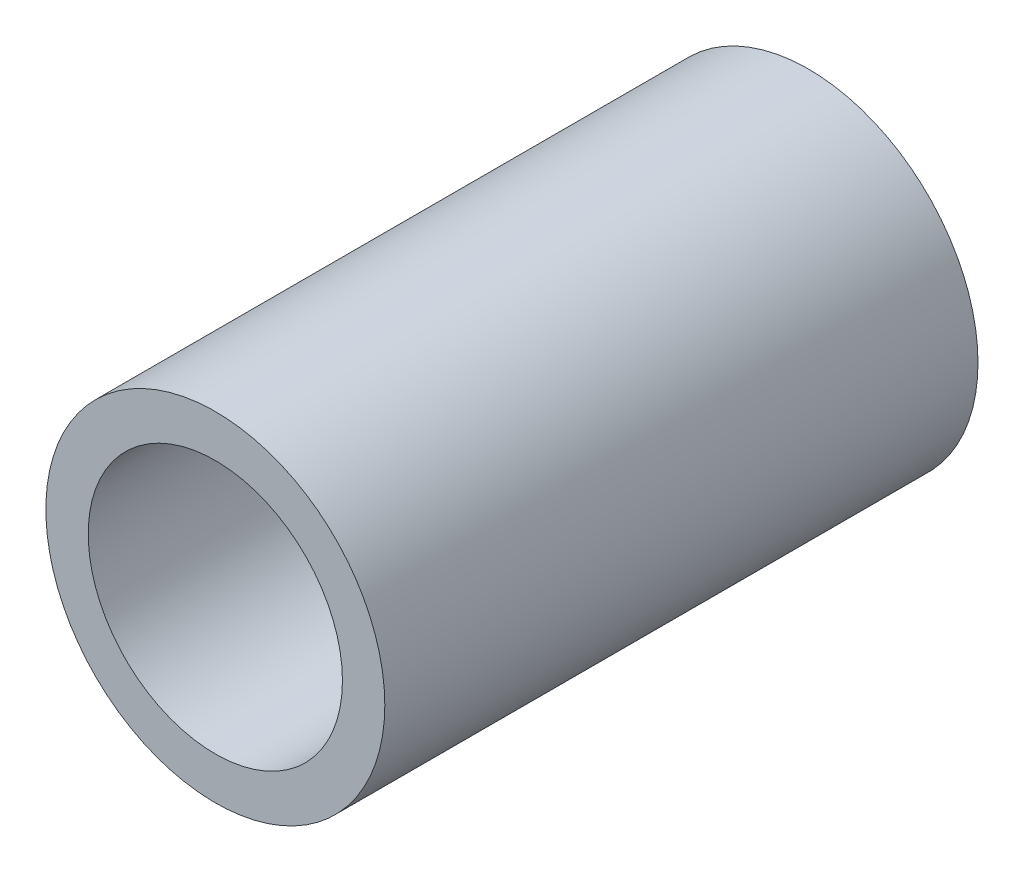
SolidWorks part; units mm, degrees
ref_plane "Front Plane" through (0, 0, 0) normal (0, 0, 1) x (1, 0, 0)
ref_plane "Top Plane" through (0, 0, 0) normal (0, 1, 0) x (1, 0, 0)
ref_plane "Right Plane" through (0, 0, 0) normal (1, 0, 0) x (0, 0, -1)
sketch "Sketch1" plane through (0, 0, 0) normal (0, 0, 1) x (1, 0, 0)
  circle A0 centre (0, 0) radius 6.35
  circle A1 centre (0, 0) radius 4.7625
  dimension "D1" = 12.7
  dimension "ID" = 9.525
extrude "Extrude1" add sketch "Sketch1" along normal mid plane 22.225
sketch "Sketch2" plane through (0, 0, 0) normal (1, 0, 0) x (0, 0, -1)
  line L0 (-11.1125, -4.7625) -> (11.1125, -4.7625) construction
  line L3 (11.1125, 4.7625) -> (-11.1125, 4.7625) construction
  line L5 (-11.1125, -4.7625) -> (11.1125, -4.7625)
  line L6 (11.1125, 4.7625) -> (-11.1125, 4.7625)
sketch "Sketch4" plane through (0, 0, 11.1125) normal (0, 0, 1) x (1, 0, 0)
  line L0 (0, 0) -> (-3.3676, 3.3676)
  line L1 (0, -13.97) -> (0, 13.97) construction
  circle A0 centre (0, 0) radius 4.7625 construction
  dimension "D1" = 45
